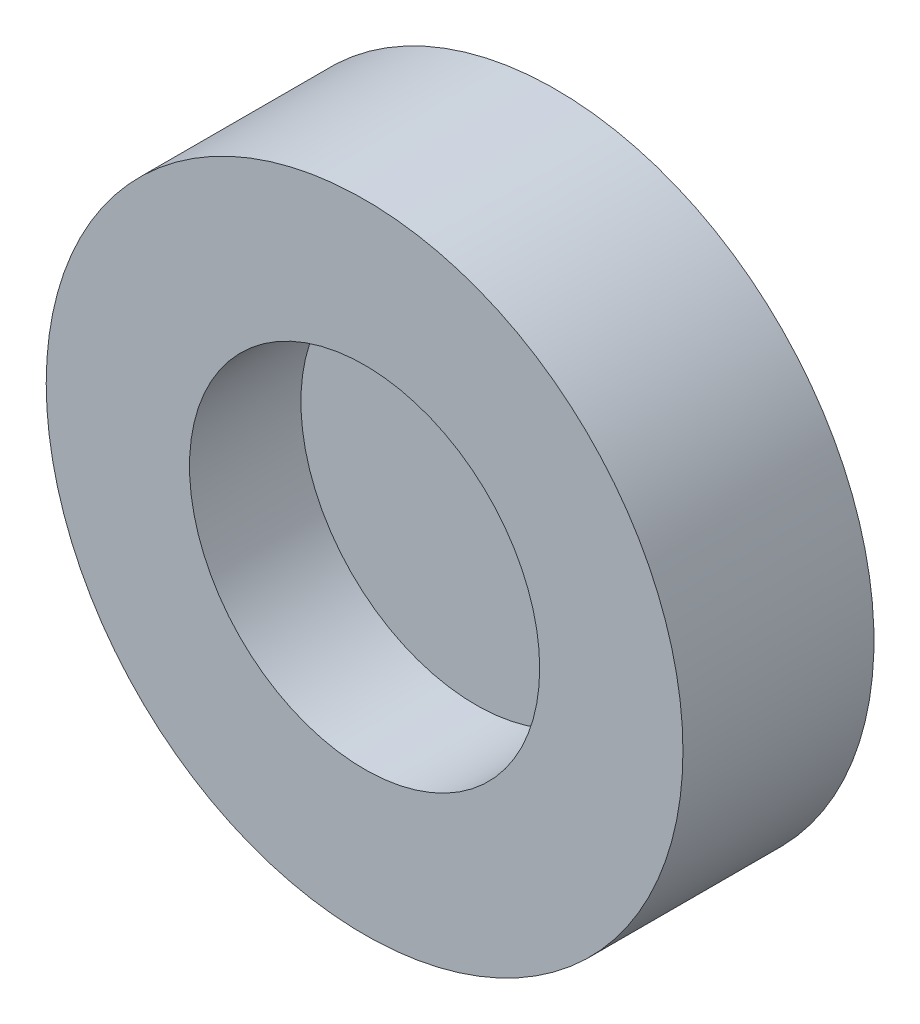
SolidWorks part; units mm, degrees
ref_plane "Front Plane" through (0, 0, 0) normal (0, 0, 1) x (1, 0, 0)
ref_plane "Top Plane" through (0, 0, 0) normal (0, 1, 0) x (1, 0, 0)
ref_plane "Right Plane" through (0, 0, 0) normal (1, 0, 0) x (0, 0, -1)
sketch "Sketch1" plane through (0, 0, 0) normal (0, 0, 1) x (1, 0, 0)
  circle A0 centre (0, 0) radius 20
  circle A1 centre (0, 0) radius 11
  dimension "D1" = 22
  dimension "D2" = 40
extrude "Boss-Extrude1" add sketch "Sketch1" along normal blind 7
sketch "Sketch2" plane through (0, 0, 0) normal (0, 0, -1) x (-1, 0, 0)
  circle A0 centre (0, 0) radius 20
  dimension "D1" = 40
extrude "Boss-Extrude2" add sketch "Sketch2" along normal blind 5
